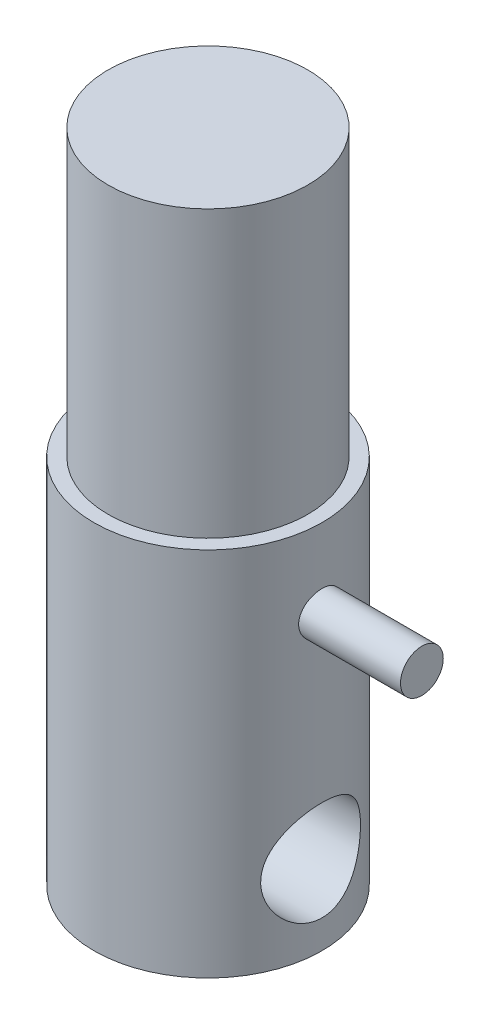
SolidWorks part; units mm, degrees
material "ABS"
ref_plane "Front Plane" through (0, 0, 0) normal (0, 0, 1) x (1, 0, 0)
ref_plane "Top Plane" through (0, 0, 0) normal (0, 1, 0) x (1, 0, 0)
ref_plane "Right Plane" through (0, 0, 0) normal (1, 0, 0) x (0, 0, -1)
sketch "Sketch2" plane through (0, 0, 0) normal (0, 1, 0) x (1, 0, 0)
  circle A0 centre (0, 0) radius 8
  dimension "D1" = 16
extrude "Boss-Extrude1" add sketch "Sketch2" along normal blind 26
sketch "Sketch3" plane through (0, 0, 0) normal (1, 0, 0) x (0, 0, -1)
  circle A0 centre (0, 5.5) radius 3.5
  dimension "D1" = 7
  dimension "D2" = 5.5
extrude "Cut-Extrude1" cut sketch "Sketch3" against normal through all both and the other way through all
sketch "Sketch4" plane through (0, 0, 0) normal (1, 0, 0) x (0, 0, -1)
  line L0 (0, 5.5) -> (0, 20.5) construction
  circle A0 centre (0, 20.5) radius 1.5
  dimension "D2" = 3
  dimension "D1" = 15
extrude "Boss-Extrude2" add sketch "Sketch4" along normal blind 15
ref_plane "Plane1" through (10, 0, 0) normal (1, 0, 0) x (0, 0, -1)
sketch "Sketch5" plane through (10, 0, 0) normal (1, 0, 0) x (0, 0, -1)
  point P0 (0, 20.5)
sketch "Sketch6" plane through (0, 26, 0) normal (0, 1, 0) x (1, 0, 0)
  circle A0 centre (0, 0) radius 7
  dimension "D1" = 14
extrude "Boss-Extrude3" add sketch "Sketch6" along normal blind 20
